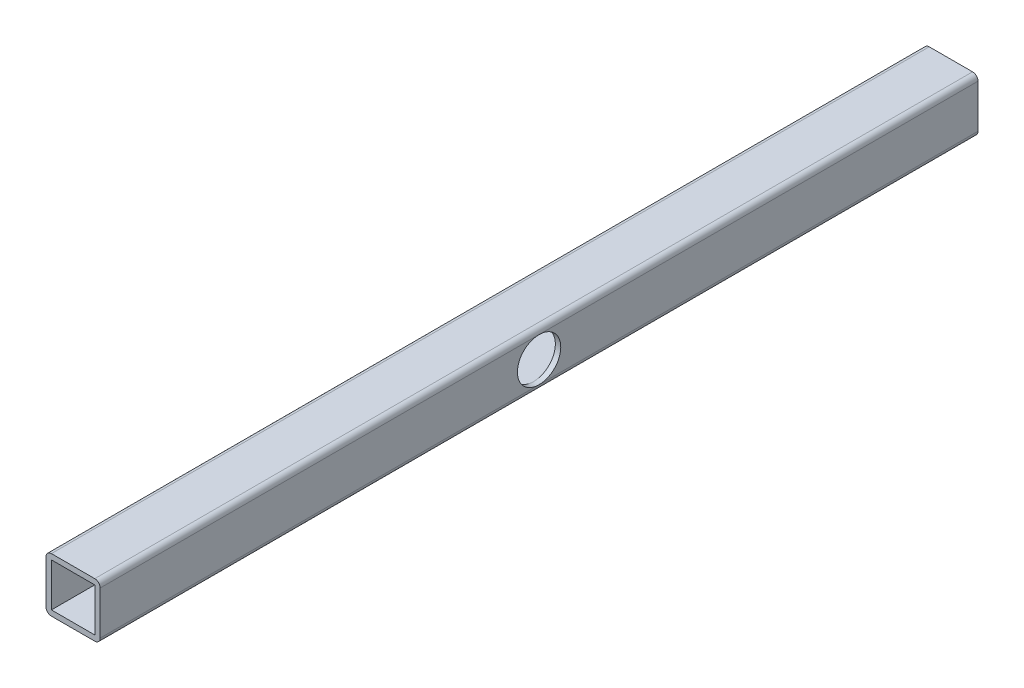
SolidWorks part; units mm, degrees
ref_plane "Front Plane" through (0, 0, 0) normal (0, 0, 1) x (1, 0, 0)
ref_plane "Top Plane" through (0, 0, 0) normal (0, 1, 0) x (1, 0, 0)
ref_plane "Right Plane" through (0, 0, 0) normal (1, 0, 0) x (0, 0, -1)
sketch "Sketch1" plane through (0, 0, 0) normal (0, 0, 1) x (1, 0, 0)
  line L1 (-60, -60) -> (60, -60)
  line L2 (-60, -60) -> (-60, 60)
  line L3 (-60, 60) -> (60, 60)
  line L4 (60, -60) -> (60, 60)
  line L5 (-60, -60) -> (60, 60) construction
  line L6 (-60, 60) -> (60, -60) construction
  point P0 (0, 0)
  dimension "D1" = 120
  dimension "D2" = 120
extrude "Boss-Extrude1" add sketch "Sketch1" along normal blind 5
sketch "Sketch2" plane through (0, 0, 5) normal (0, 0, 1) x (1, 0, 0)
  line L1 (-50, -50) -> (50, -50)
  line L2 (-50, -50) -> (-50, 50)
  line L3 (-50, 50) -> (50, 50)
  line L4 (50, -50) -> (50, 50)
  line L5 (-50, -50) -> (50, 50) construction
  line L6 (-50, 50) -> (50, -50) construction
  point P0 (0, 0)
  dimension "D1" = 100
  dimension "D2" = 100
extrude "Extrude-Thin1" add sketch "Sketch2" along normal blind 1620 thin thin type one direction reverse wall 10
sketch "Sketch3" plane through (0, 0, 1625) normal (0, 0, 1) x (1, 0, 0)
  line L0 (60, -60) -> (60, 60) construction
  line L1 (-60, -60) -> (60, -60) construction
  line L2 (-60, 60) -> (-60, -60) construction
  line L3 (60, 60) -> (-60, 60) construction
  line L4 (60, -60) -> (60, 60)
  line L5 (-60, -60) -> (60, -60)
  line L6 (-60, 60) -> (-60, -60)
  line L7 (60, 60) -> (-60, 60)
fillet "Fillet1" radius 10 4 edges at (50, -50, 815) (-50, -50, 815) (50, 50, 815) (-50, 50, 815)
sketch "Sketch4" plane through (60, 0, 0) normal (1, 0, 0) x (0, 0, -1)
  line L1 (-5, 74) -> (23.9712, 74)
  line L2 (-5, 74) -> (-5, -65.8867)
  line L3 (-5, -65.8867) -> (23.9712, -65.8867)
  line L4 (23.9712, 74) -> (23.9712, -65.8867)
extrude "Cut-Extrude1" cut sketch "Sketch4" against normal through all
sketch "Sketch5" plane through (50, 0, 0) normal (1, 0, 0) x (0, 0, -1)
  line L1 (-1625, -40) -> (-1625, 40) construction
  circle A0 centre (-815, 0) radius 40
  dimension "D1" = 80
  dimension "D2" = 810
extrude "Cut-Extrude2" cut sketch "Sketch5" against normal through all
